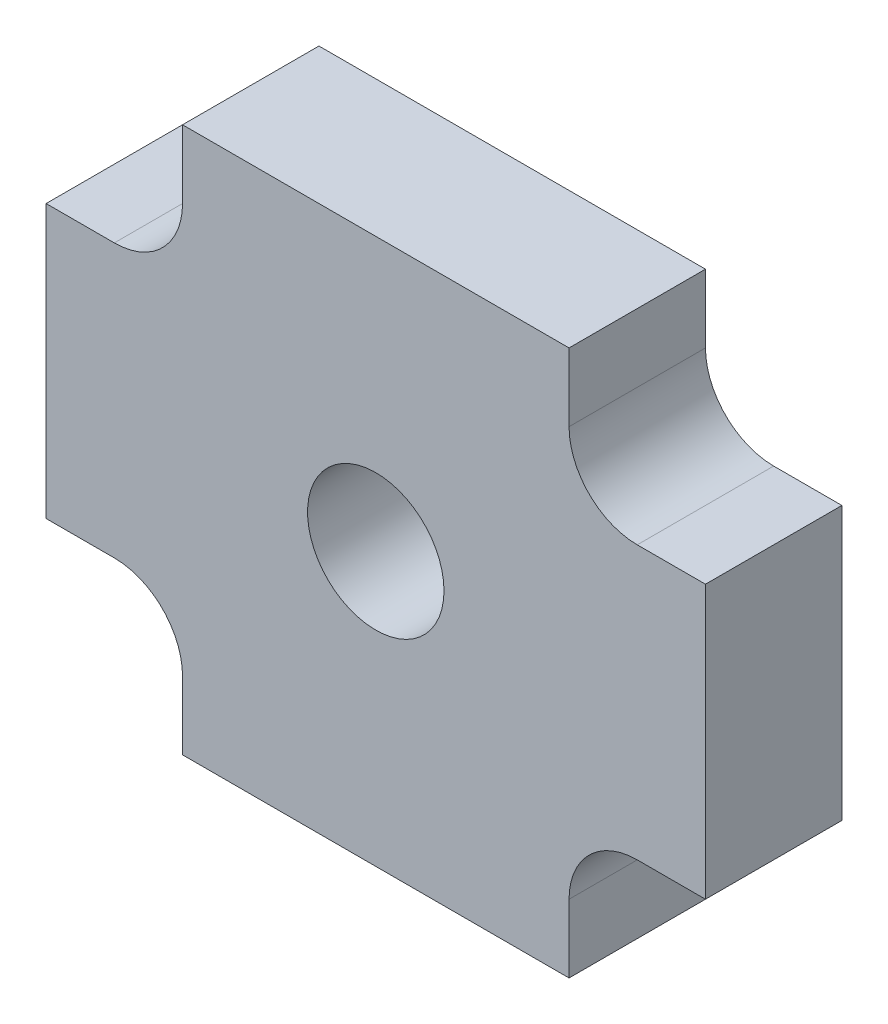
SolidWorks part; units mm, degrees
ref_plane "Alzado" through (0, 0, 0) normal (0, 0, 1) x (1, 0, 0)
ref_plane "Planta" through (0, 0, 0) normal (0, 1, 0) x (1, 0, 0)
ref_plane "Vista lateral" through (0, 0, 0) normal (1, 0, 0) x (0, 0, -1)
sketch "Model" plane through (0, 0, 0) normal (0, 0, 1) x (1, 0, 0)
  line L0 (132.1048, 242.3415) -> (132.1048, 236.3415)
  line L1 (135.1048, 233.3415) -> (143.6048, 233.3415)
  line L2 (146.6048, 236.3415) -> (146.6048, 242.3415)
  line L3 (143.6048, 245.3415) -> (135.1048, 245.3415)
  line L4 (135.1048, 243.8415) -> (135.1048, 245.3415)
  line L5 (133.6048, 242.3415) -> (132.1048, 242.3415)
  line L6 (133.6048, 236.3415) -> (132.1048, 236.3415)
  line L7 (135.1048, 234.8415) -> (135.1048, 233.3415)
  line L8 (145.1048, 236.3415) -> (146.6048, 236.3415)
  line L9 (143.6048, 234.8415) -> (143.6048, 233.3415)
  line L10 (145.1048, 242.3415) -> (146.6048, 242.3415)
  line L11 (143.6048, 243.8415) -> (143.6048, 245.3415)
  circle A0 centre (139.3548, 239.3415) radius 1.5
  arc A1 (143.6048, 243.8415) -> (145.1048, 242.3415) centre (145.1048, 243.8415) ccw
  arc A2 (145.1048, 236.3415) -> (143.6048, 234.8415) centre (145.1048, 234.8415) ccw
  arc A3 (135.1048, 234.8415) -> (133.6048, 236.3415) centre (133.6048, 234.8415) ccw
  arc A4 (133.6048, 242.3415) -> (135.1048, 243.8415) centre (133.6048, 243.8415) ccw
extrude "Saliente-Extruir1" add sketch "Model" along normal blind 3
